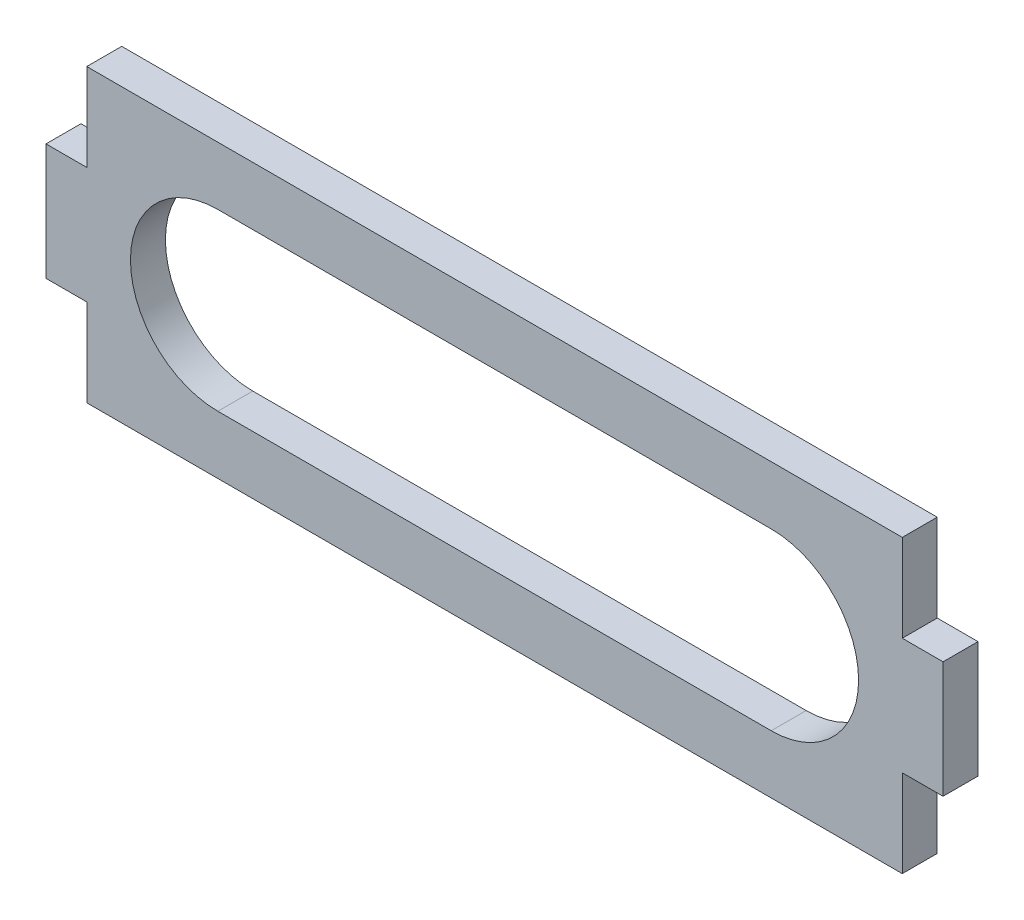
SolidWorks part; units mm, degrees
material "Teak"
ref_plane "Front Plane" through (0, 0, 0) normal (0, 0, 1) x (1, 0, 0)
ref_plane "Top Plane" through (0, 0, 0) normal (0, 1, 0) x (1, 0, 0)
ref_plane "Right Plane" through (0, 0, 0) normal (1, 0, 0) x (0, 0, -1)
sketch "Sketch1" plane through (0, 0, 0) normal (0, 0, 1) x (1, 0, 0)
  point P0 (0, 0)
  line B0 (117.5, -10) -> (22.5, -10)
  line B1 (22.5, -40) -> (117.5, -40)
  line B2 (140, 0) -> (0, 0)
  line B3 (0, 0) -> (0, -15)
  line B4 (0, -15) -> (-7, -15)
  line B5 (-7, -15) -> (-7, -35)
  line B6 (-7, -35) -> (0, -35)
  line B7 (0, -35) -> (0, -50)
  line B8 (0, -50) -> (140, -50)
  line B9 (140, -50) -> (140, -35)
  line B10 (140, -35) -> (147, -35)
  line B11 (147, -35) -> (147, -15)
  line B12 (147, -15) -> (140, -15)
  line B13 (140, -15) -> (140, 0)
  arc B14 (22.5, -10) -> (22.5, -40) centre (22.5, -25) ccw
  arc B15 (117.5, -40) -> (117.5, -10) centre (117.5, -25) ccw
sketch_block_instance "Block1-1"
sketch_block "Block1"
extrude "Boss-Extrude1" add sketch "Sketch1" along normal blind 6
